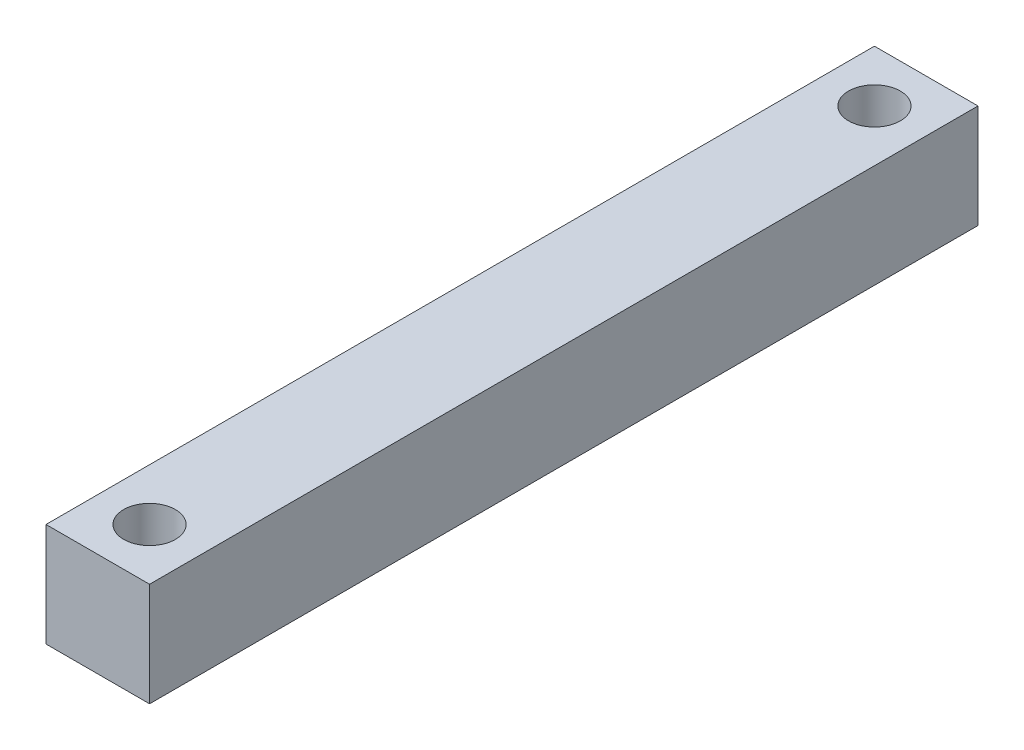
SolidWorks part; units mm, degrees
ref_plane "Front" through (0, 0, 0) normal (0, 0, 1) x (1, 0, 0)
ref_plane "Top" through (0, 0, 0) normal (0, 1, 0) x (1, 0, 0)
ref_plane "Right" through (0, 0, 0) normal (1, 0, 0) x (0, 0, -1)
sketch "Sketch1" plane through (0, 0, 0) normal (0, 0, 1) x (1, 0, 0)
  line L1 (-5, 5) -> (5, 5)
  line L2 (-5, 5) -> (-5, -5)
  line L3 (-5, -5) -> (5, -5)
  line L4 (5, 5) -> (5, -5)
  line L5 (-5, 5) -> (5, -5) construction
  line L6 (-5, -5) -> (5, 5) construction
  point P0 (0, 0)
  dimension "D1" = 10
  dimension "D2" = 10
extrude "Boss-Extrude1" add sketch "Sketch1" along normal mid plane 80
sketch "Sketch2" plane through (0, 0, 0) normal (0, 1, 0) x (1, 0, 0)
  line L3 (-50, 0) -> (50, 0) construction
  line L4 (5, -40) -> (-5, -40) construction
  circle A2 centre (0, -35) radius 2.5
  circle A3 centre (0, 35) radius 2.5
  dimension "D2" = 5
  dimension "D1" = 5
extrude "Cut-Extrude1" cut sketch "Sketch2" against normal through all both and the other way through all
